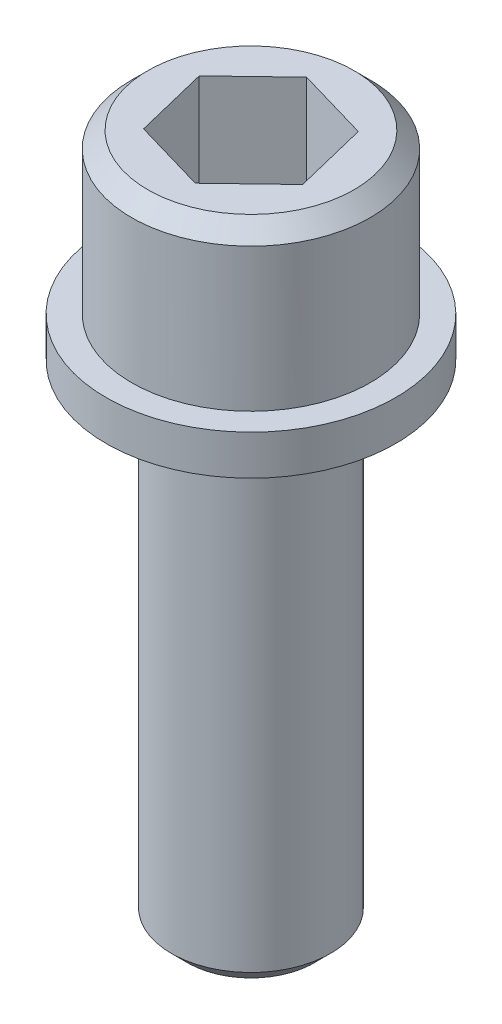
SolidWorks part; units mm, degrees
ref_plane "Front Plane" through (0, 0, 0) normal (0, 0, 1) x (1, 0, 0)
ref_plane "Top Plane" through (0, 0, 0) normal (0, 1, 0) x (1, 0, 0)
ref_plane "Right Plane" through (0, 0, 0) normal (1, 0, 0) x (0, 0, -1)
sketch "Sketch1" plane through (0, 0, 0) normal (0, 0, 1) x (1, 0, 0)
  line L1 (0, 41.275) -> (7.1437, 41.275)
  line L2 (7.1437, 41.275) -> (7.1437, 31.75)
  line L3 (7.1437, 31.75) -> (8.6741, 31.75)
  line L4 (8.6741, 31.75) -> (8.6741, 29.3624)
  line L5 (8.6741, 29.3624) -> (4.7625, 29.3624)
  line L6 (4.7625, 29.3624) -> (4.7625, 0)
  line L7 (4.7625, 0) -> (0, 0)
  line L8 (0, 41.275) -> (0, 0) construction
  line L9 (0, 0) -> (0, 41.275)
  dimension "D1" = 41.275
  dimension "D2" = 2.3876
  dimension "D3" = 9.525
  dimension "D4" = 14.2875
  dimension "D5" = 17.3482
  dimension "D6" = 9.525
revolve "Revolve2" add sketch "Sketch1" angle 360 about L8
sketch "Sketch4" plane through (0, 41.275, 0) normal (0, 1, 0) x (1, 0, 0)
  line L1 (4.3651, -1.2698) -> (3.2823, 3.1454)
  line L2 (3.2823, 3.1454) -> (-1.0828, 4.4152)
  line L3 (-1.0828, 4.4152) -> (-4.3651, 1.2698)
  line L4 (-4.3651, 1.2698) -> (-3.2823, -3.1454)
  line L5 (-3.2823, -3.1454) -> (1.0828, -4.4152)
  line L6 (1.0828, -4.4152) -> (4.3651, -1.2698)
  circle A0 centre (0, 0) radius 3.937 construction
  dimension "D1" = 7.874
extrude "Cut-Extrude2" cut sketch "Sketch4" against normal blind 6.35
chamfer "Chamfer1" distance 0.9652 angle 45 2 edges at (-4.7625, 0, 0) (-7.1437, 41.275, 0)
